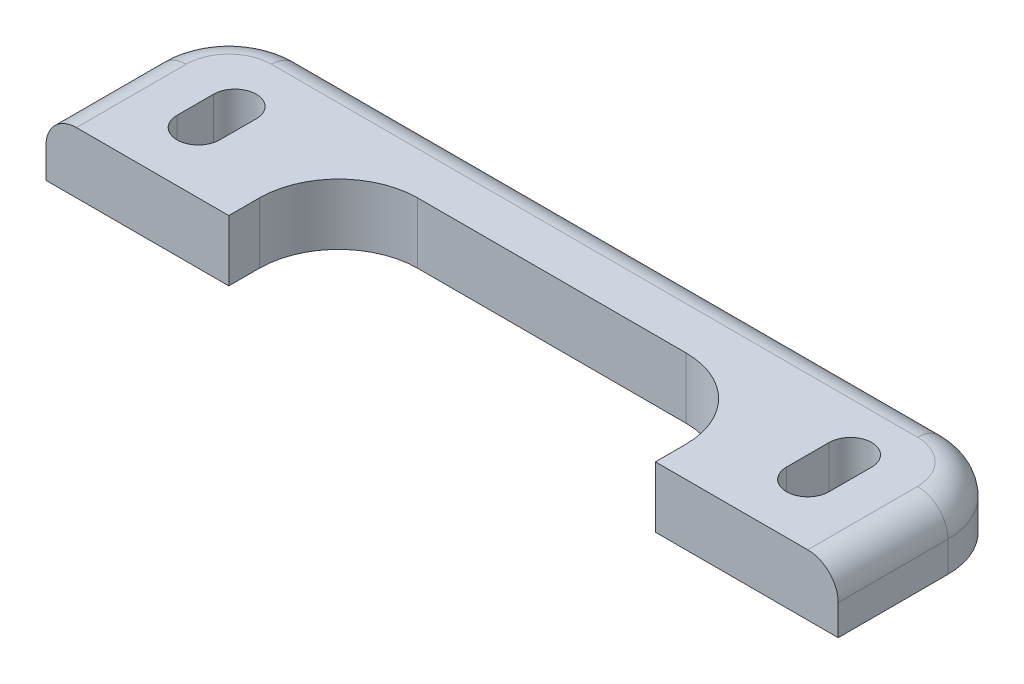
SolidWorks part; units mm, degrees
ref_plane "Front Plane" through (0, 0, 0) normal (0, 0, 1) x (1, 0, 0)
ref_plane "Top Plane" through (0, 0, 0) normal (0, 1, 0) x (1, 0, 0)
ref_plane "Right Plane" through (0, 0, 0) normal (1, 0, 0) x (0, 0, -1)
sketch "Sketch3" plane through (0, 0, 0) normal (0, 1, 0) x (1, 0, 0)
  line L0 (-32.5, 12) -> (-32.5, 22)
  line L1 (-32.5, 0) -> (32.5, 0)
  line L2 (-32.5, 0) -> (-32.5, 12)
  line L3 (-22.5, 22) -> (22.5, 22)
  line L4 (32.5, 0) -> (32.5, 12)
  line L5 (-32.5, 22) -> (-22.5, 22)
  line L6 (22.5, 22) -> (32.5, 22)
  line L7 (32.5, 22) -> (32.5, 12)
  point P4 (0, 0)
  point P8 (32.5, 22)
  point P11 (-32.5, 22)
  dimension "D1" = 65
  dimension "D2" = 22
extrude "Boss-Extrude1" add sketch "Sketch3" along normal blind 5
sketch "Sketch4" plane through (0, 5, 0) normal (0, 1, 0) x (1, 0, 0)
  line L0 (-32.5, 0) -> (32.5, 0) construction
  line L1 (-17.5, 0) -> (17.5, 0)
  line L2 (-17.5, 0) -> (-17.5, 2.5)
  line L3 (-11, 9) -> (11, 9)
  line L4 (17.5, 0) -> (17.5, 2.5)
  line L5 (-17.5, 1.25) -> (-32.5, 1.25) construction
  line L6 (-32.5, 22) -> (-32.5, 0) construction
  line L7 (17.5, 1.25) -> (32.5, 1.25) construction
  line L8 (32.5, 0) -> (32.5, 22) construction
  line L9 (0, 9) -> (0, 22) construction
  line L10 (32.5, 22) -> (-32.5, 22) construction
  arc A0 (11, 9) -> (17.5, 2.5) centre (11, 2.5) cw
  arc A1 (-17.5, 2.5) -> (-11, 9) centre (-11, 2.5) cw
  circle A2 centre (-25, 5) radius 1.75
  circle A3 centre (0, 15.5) radius 1.75
  circle A4 centre (25, 5) radius 1.75
  point P8 (17.5, 9)
  point P11 (-17.5, 9)
  point P12 (0, 9)
  point P32 (-25, 1.4765)
  point P33 (25, 1.25)
  point P35 (-24.3964, 2.1265)
  point P36 (-25, 1.25)
  point P40 (0.5117, 15.5)
  point P42 (0, 15.5)
  dimension "D3" = 6.5
  dimension "D4" = 3.5
  dimension "D5" = 3.75
  dimension "D1" = 9
  dimension "D2" = 35
  dimension "D6" = 2.9362
  dimension "D7" = 0.5117
  dimension "D8" = 5
extrude "Cut-Extrude1" cut sketch "Sketch4" against normal blind 5
sketch "Sketch5" plane through (0, 5, 0) normal (0, 1, 0) x (1, 0, 0)
  line L0 (-26.75, 5) -> (-26.75, 8)
  line L1 (-23.25, 5) -> (-23.25, 8)
  line L2 (-26.75, 5) -> (-23.25, 5)
  line L6 (23.25, 5) -> (26.75, 5)
  line L7 (26.75, 5) -> (26.75, 8.5)
  line L8 (23.25, 5) -> (23.25, 8.5)
  circle A0 centre (-25, 5) radius 1.75 construction
  arc A1 (-26.75, 8) -> (-23.25, 8) centre (-25, 8) cw
  circle A3 centre (25, 5) radius 1.75 construction
  arc A4 (23.25, 8.5) -> (26.75, 8.5) centre (25, 8.5) cw
  dimension "D1" = 3
  dimension "D3" = 1.75
  dimension "D2" = 3.5
  dimension "D5" = 3.5
extrude "Cut-Extrude2" cut sketch "Sketch5" against normal up to surface (5 mm away) up to face at (25, 0, -3.25)
sketch "Sketch6" plane through (0, 5, 0) normal (0, 1, 0) x (1, 0, 0)
  circle A0 centre (0, 15.5) radius 1.75 construction
  circle A1 centre (0, 15.5) radius 1.75
extrude "Boss-Extrude2" add sketch "Sketch6" against normal up to surface (5 mm away) up to face at (-25, 0, -6.5)
sketch "Sketch7" plane through (0, 5, 0) normal (0, 1, 0) x (1, 0, 0)
  line L0 (32.5, 0) -> (32.5, 22) construction
  line L1 (-32.5, 22) -> (32.5, 22)
  line L2 (-32.5, 22) -> (-32.5, 15)
  line L3 (-32.5, 15) -> (32.5, 15)
  line L4 (32.5, 22) -> (32.5, 15)
  dimension "D1" = 7
extrude "Cut-Extrude3" cut sketch "Sketch7" against normal blind 10
fillet "Fillet1" radius 6 2 edges at (32.5, 2.5, -15) (-32.5, 2.5, -15)
fillet "Fillet2" radius 2.5 5 edges at (32.5, 5, -4.5) (30.7426, 5, -13.2426) (0, 5, -15) (-30.7426, 5, -13.2426) (-32.5, 5, -4.5)
